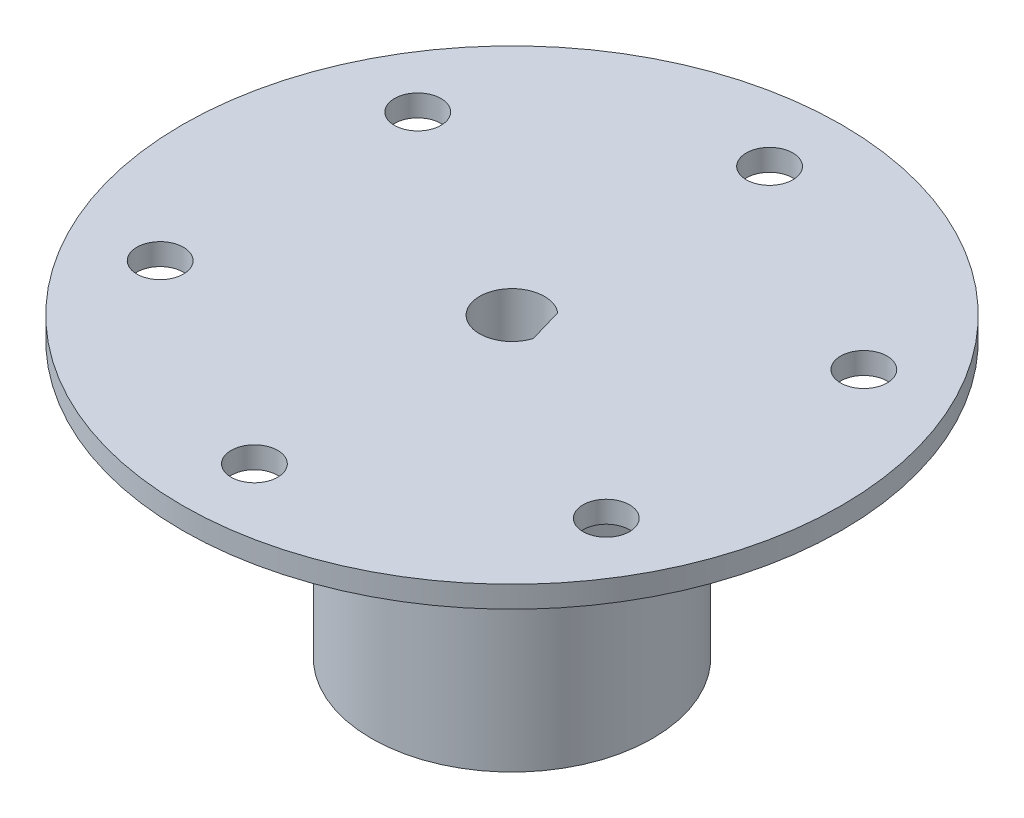
SolidWorks part; units mm, degrees
ref_plane "Front" through (0, 0, 0) normal (0, 0, 1) x (1, 0, 0)
ref_plane "Top" through (0, 0, 0) normal (0, 1, 0) x (1, 0, 0)
ref_plane "Right" through (0, 0, 0) normal (1, 0, 0) x (0, 0, -1)
sketch "Sketch1" plane through (0, 0, 0) normal (0, 1, 0) x (1, 0, 0)
  circle A1 centre (0, 0) radius 30.48
  circle A2 centre (0, -23.8125) radius 2.1526
  circle A3 centre (20.6222, -11.9062) radius 2.1526
  circle A4 centre (20.6222, 11.9063) radius 2.1526
  circle A5 centre (0, 23.8125) radius 2.1526
  circle A6 centre (-20.6222, 11.9062) radius 2.1527
  circle A7 centre (-20.6222, -11.9062) radius 2.1527
extrude "Boss-Extrude1" add sketch "Sketch1" along normal blind 2
sketch "Sketch2" plane through (0, 2, 0) normal (0, 1, 0) x (1, 0, 0)
  line L0 (2.8645, -0.8913) -> (1.932, 2.295)
  circle A0 centre (0, 0) radius 3
  dimension "D1" = 3.32
extrude "Cut-Extrude1" cut sketch "Sketch2" against normal blind 10 contours L0 A0
sketch "Sketch3" plane through (0, 0, 0) normal (0, -1, 0) x (1, 0, 0)
  line L0 (1.932, -2.295) -> (2.8645, 0.8913)
  circle A0 centre (0, 0) radius 13
  circle A1 centre (0, 0) radius 3.1104
  arc M1 (1.932, -2.295) -> (2.8645, 0.8913) centre (0, 0) cw
  line M2 (2.8645, 0.8913) -> (1.932, -2.295)
  dimension "D1" = 26
extrude "Boss-Extrude2" add sketch "Sketch3" along normal blind 25.4 contours A0 A1 | A1 M2 M1
